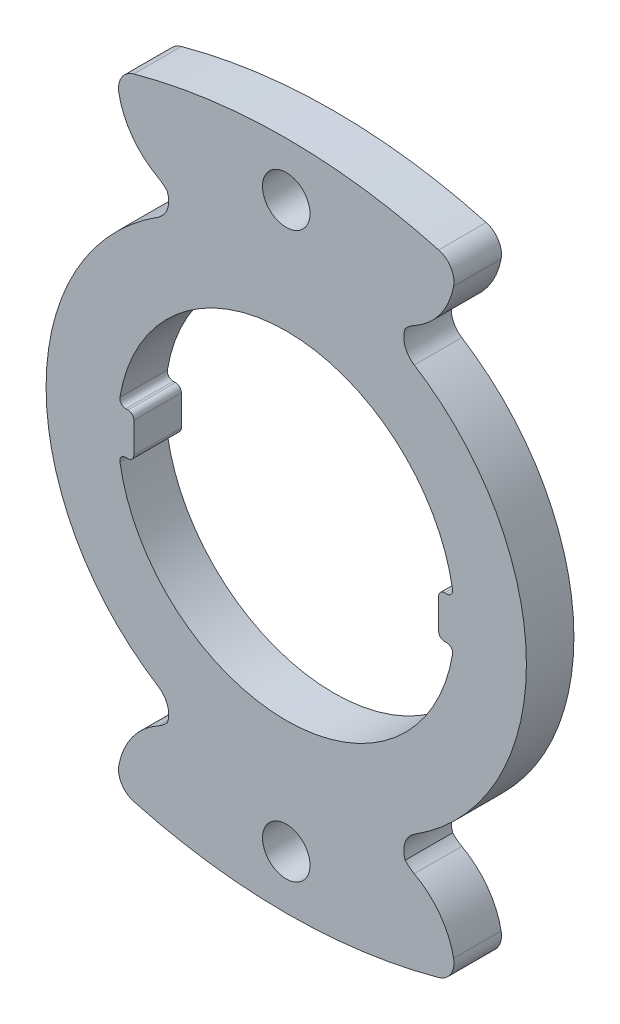
SolidWorks part; units mm, degrees
ref_plane "Front Plane" through (0, 0, 0) normal (0, 0, 1) x (1, 0, 0)
ref_plane "Top Plane" through (0, 0, 0) normal (0, 1, 0) x (1, 0, 0)
ref_plane "Right Plane" through (0, 0, 0) normal (1, 0, 0) x (0, 0, -1)
sketch "Sketch3" plane through (0, 0, 0) normal (0, 0, 1) x (1, 0, 0)
  line L0 (-14.2, 0) -> (14.2, 0) construction
  line L1 (-12.8287, 1.7747) -> (-12.8287, -1.7747)
  line L2 (-14.0887, 1.7747) -> (-12.8287, 1.7747)
  line L3 (-12.8287, -1.7747) -> (-14.0887, -1.7747)
  line L4 (0, 21.0297) -> (0, -14.2) construction
  line L5 (12.8287, -1.7747) -> (14.0887, -1.7747)
  line L6 (12.8287, 1.7747) -> (12.8287, -1.7747)
  line L7 (14.0887, 1.7747) -> (12.8287, 1.7747)
  line L9 (0, 21.0297) -> (0, 28.2497) construction
  arc A0 (-10.777, 17.1027) -> (-10.777, -17.1027) centre (0, 0) ccw
  arc A1 (-14.0887, -1.7747) -> (14.0887, -1.7747) centre (0, 0) ccw
  arc A2 (14.0887, 1.7747) -> (-14.0887, 1.7747) centre (0, 0) ccw
  arc A7 (12.8287, 26.5208) -> (0, 28.2497) centre (0, -20.2095) ccw
  arc A8 (-12.8287, 26.5208) -> (0, 28.2497) centre (0, -20.2095) cw
  arc A9 (-12.8287, 26.5208) -> (-14.0887, 24.4898) centre (-12.3633, 24.8258) ccw
  arc A10 (-14.0887, 24.4898) -> (-10.777, 19.981) centre (-7.659, 25.7417) ccw
  arc A12 (12.8287, 26.5208) -> (14.0887, 24.4898) centre (12.3633, 24.8258) cw
  arc A14 (14.0887, 24.4898) -> (10.777, 19.981) centre (7.659, 25.7417) cw
  arc A17 (14.0887, 24.4898) -> (10.777, 19.981) centre (7.659, 25.7417) cw
  arc A18 (12.8287, 26.5208) -> (14.0887, 24.4898) centre (12.3633, 24.8258) cw
  arc A19 (12.8287, 26.5208) -> (0, 28.2497) centre (0, -20.2095) ccw
  arc A20 (-12.8287, 26.5208) -> (0, 28.2497) centre (0, -20.2095) cw
  arc A21 (12.8287, 26.5208) -> (0, 28.2497) centre (0, -20.2095) ccw
  arc A22 (-12.8287, 26.5208) -> (0, 28.2497) centre (0, -20.2095) cw
  arc A23 (10.5836, -17.223) -> (10.5836, 17.223) centre (0, 0) ccw
  arc A24 (-12.8287, 26.5208) -> (-14.0887, 24.4898) centre (-12.3633, 24.8258) ccw
  arc A25 (-14.0887, 24.4898) -> (-10.777, 19.981) centre (-7.659, 25.7417) ccw
  arc A26 (-10.777, 17.1027) -> (-10.0147, 19.3762) centre (-11.7873, 18.706) ccw
  arc A28 (-14.0887, 24.4898) -> (-10.777, 19.981) centre (-7.659, 25.7417) ccw
  arc A29 (-10.777, 19.981) -> (-10.0147, 19.3762) centre (-12.1101, 17.518) cw
  arc A30 (-12.8287, 26.5208) -> (-14.0887, 24.4898) centre (-12.3633, 24.8258) ccw
  arc A32 (14.0887, 24.4898) -> (10.777, 19.981) centre (7.659, 25.7417) cw
  arc A33 (12.8287, 26.5208) -> (14.0887, 24.4898) centre (12.3633, 24.8258) cw
  arc A34 (12.8287, 26.5208) -> (0, 28.2497) centre (0, -20.2095) ccw
  arc A35 (-12.8287, 26.5208) -> (0, 28.2497) centre (0, -20.2095) cw
  arc A36 (-10.777, 19.981) -> (-10.0147, 19.3762) centre (-12.1101, 17.518) cw
  arc A37 (-10.777, 17.1027) -> (-10.0147, 19.3762) centre (-11.7873, 18.706) ccw
  arc A38 (12.8287, 26.5208) -> (0, 28.2497) centre (0, -20.2095) ccw
  arc A39 (-12.8287, 26.5208) -> (0, 28.2497) centre (0, -20.2095) cw
  arc A40 (-12.8287, 26.5208) -> (-14.0887, 24.4898) centre (-12.3633, 24.8258) ccw
  arc A41 (-14.0887, 24.4898) -> (-10.777, 19.981) centre (-7.659, 25.7417) ccw
  arc A42 (12.8287, 26.5208) -> (14.0887, 24.4898) centre (12.3633, 24.8258) cw
  arc A43 (10.777, 19.981) -> (10.0147, 19.3762) centre (12.1101, 17.518) ccw
  arc A44 (10.777, 17.1027) -> (10.0147, 19.3762) centre (11.7873, 18.706) cw
  arc A45 (10.777, 19.981) -> (10.0147, 19.3762) centre (12.1101, 17.518) ccw
  arc A46 (14.0887, 24.4898) -> (10.777, 19.981) centre (7.659, 25.7417) cw
  arc A47 (10.777, 17.1027) -> (10.0147, 19.3762) centre (11.7873, 18.706) cw
  arc A48 (14.0887, 24.4898) -> (10.777, 19.981) centre (7.659, 25.7417) cw
  arc A49 (12.8287, 26.5208) -> (14.0887, 24.4898) centre (12.3633, 24.8258) cw
  arc A50 (12.8287, 26.5208) -> (0, 28.2497) centre (0, -20.2095) ccw
  arc A51 (-12.8287, 26.5208) -> (0, 28.2497) centre (0, -20.2095) cw
  arc A52 (12.8287, 26.5208) -> (0, 28.2497) centre (0, -20.2095) ccw
  arc A53 (-12.8287, 26.5208) -> (0, 28.2497) centre (0, -20.2095) cw
  arc A54 (-12.8287, 26.5208) -> (-14.0887, 24.4898) centre (-12.3633, 24.8258) ccw
  arc A55 (-14.0887, 24.4898) -> (-10.777, 19.981) centre (-7.659, 25.7417) ccw
  arc A56 (-14.0887, 24.4898) -> (-10.777, 19.981) centre (-7.659, 25.7417) ccw
  arc A57 (-12.8287, 26.5208) -> (-14.0887, 24.4898) centre (-12.3633, 24.8258) ccw
  arc A58 (14.0887, 24.4898) -> (10.777, 19.981) centre (7.659, 25.7417) cw
  arc A59 (12.8287, 26.5208) -> (14.0887, 24.4898) centre (12.3633, 24.8258) cw
  arc A60 (12.8287, 26.5208) -> (0, 28.2497) centre (0, -20.2095) ccw
  arc A61 (-12.8287, 26.5208) -> (0, 28.2497) centre (0, -20.2095) cw
  arc A62 (-10.777, -17.1027) -> (-10.0147, -19.3762) centre (-11.7873, -18.706) cw
  arc A63 (-10.777, -19.981) -> (-10.0147, -19.3762) centre (-12.1101, -17.518) ccw
  arc A64 (10.777, -17.1027) -> (10.0147, -19.3762) centre (11.7873, -18.706) ccw
  arc A65 (10.777, -19.981) -> (10.0147, -19.3762) centre (12.1101, -17.518) cw
  arc A66 (14.0887, -24.4898) -> (10.777, -19.981) centre (7.659, -25.7417) ccw
  arc A67 (12.8287, -26.5208) -> (14.0887, -24.4898) centre (12.3633, -24.8258) ccw
  arc A68 (12.8287, -26.5208) -> (0, -28.2497) centre (0, 20.2095) cw
  arc A69 (-12.8287, -26.5208) -> (0, -28.2497) centre (0, 20.2095) ccw
  arc A70 (-12.8287, -26.5208) -> (-14.0887, -24.4898) centre (-12.3633, -24.8258) cw
  arc A71 (-14.0887, -24.4898) -> (-10.777, -19.981) centre (-7.659, -25.7417) cw
  point P9 (-12.8287, 0)
  point P45 (13.857, 25.7524)
  dimension "D2" = 40.43
  dimension "D3" = 14.2
  dimension "D7" = 48.4591
  dimension "D8" = 1.7577
  dimension "D9" = 6.5504
  dimension "D10" = 1.895
  dimension "D11" = 2.8006
  dimension "D4" = 12.8287
  dimension "D5" = 14.0887
  dimension "D6" = 7.22
  dimension "D12" = 10.0147
  dimension "D13" = 10.5836
  dimension "D14" = 10.777
extrude "Boss-Extrude2" add sketch "Sketch3" along normal blind 4
fillet "Fillet1" radius 0.5 4 edges at (12.8287, 1.7747, 2) (12.8287, -1.7747, 2) (-12.8287, -1.7747, 2) (-12.8287, 1.7747, 2)
fillet "Fillet2" radius 0.5 4 edges at (-14.0887, 1.7747, 2) (-14.0887, -1.7747, 2) (14.0887, 1.7747, 2) (14.0887, -1.7747, 2)
sketch "Sketch4" plane through (0, 0, 4) normal (0, 0, 1) x (1, 0, 0)
  line L0 (0, 28.2497) -> (0, 23.7497) construction
  line L1 (-20.7002, 0) -> (23.0699, 0) construction
  arc A0 (12.8287, 26.5208) -> (-12.8287, 26.5208) centre (0, -20.2095) ccw construction
  circle A1 centre (0, 23.7497) radius 2
  circle A2 centre (0, -23.7497) radius 2
  dimension "D2" = 4
  dimension "D1" = 4.5
extrude "Cut-Extrude1" cut sketch "Sketch4" against normal through all both
